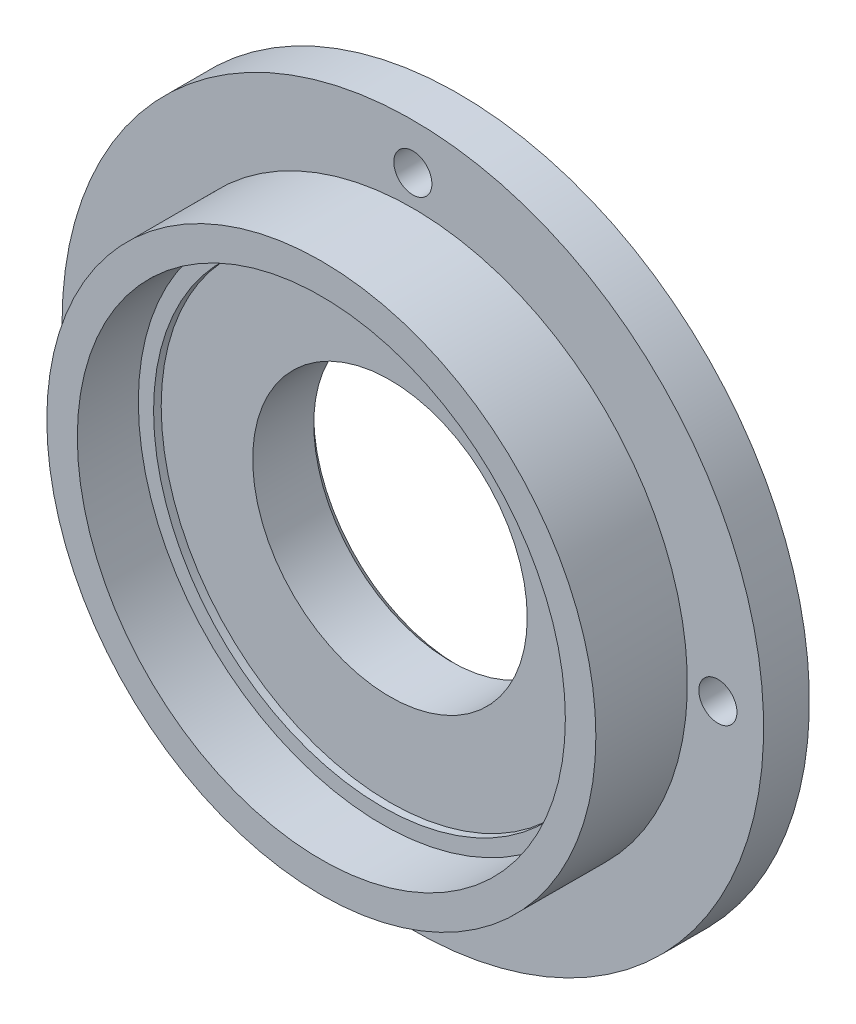
SolidWorks part; units mm, degrees
material "6061-T6 (SS)"
ref_plane "前视基准面" through (0, 0, 0) normal (0, 0, 1) x (1, 0, 0)
ref_plane "上视基准面" through (0, 0, 0) normal (0, 1, 0) x (1, 0, 0)
ref_plane "右视基准面" through (0, 0, 0) normal (1, 0, 0) x (0, 0, -1)
sketch "草图1" plane through (0, 0, 0) normal (0, 0, 1) x (1, 0, 0)
  circle A1 centre (0, 0) radius 18
  dimension "D2" = 36
extrude "凸台-拉伸3" add sketch "草图1" along normal blind 9
sketch "草图4" plane through (0, 0, 9) normal (0, 0, 1) x (1, 0, 0)
  circle A0 centre (0, 0) radius 16
  dimension "D1" = 32
extrude "切除-拉伸1" cut sketch "草图4" against normal blind 4
sketch "草图5" plane through (0, 0, 5) normal (0, 0, 1) x (1, 0, 0)
  circle A0 centre (0, 0) radius 15
  dimension "D1" = 30
extrude "切除-拉伸2" cut sketch "草图5" against normal blind 0.5
sketch "草图7" plane through (0, 0, 4.5) normal (0, 0, 1) x (1, 0, 0)
  circle A0 centre (0, 0) radius 9
  dimension "D1" = 18
extrude "切除-拉伸3" cut sketch "草图7" against normal through all
sketch "草图8" [suppressed] plane through (0, 0, 0) normal (0, 0, -1) x (-1, 0, 0)
  point P0 (0, 12)
  point P4 (12, 0)
  point P5 (0, -12)
  point P6 (-12, 0)
  point P7 (0, 0)
  dimension "D2" = 12
  dimension "D1" = 4
hole_wizard "M3 螺纹孔1" [suppressed] positions "草图9" profile "草图10" tap size "M3" standard "GB"
sketch "草图9" [suppressed] plane through (0, 0, 0) normal (0, 0, -1) x (-1, 0, 0)
  point P0 (0, 12)
  point P3 (-12, 0)
  point P6 (0, -12)
  point P9 (12, 0)
sketch "草图10" plane through (0, 12, 0) normal (1, 0, 0) x (0, 1, 0)
  line L0 (0, 0) -> (0, 3)
  line L1 (0, 3) -> (1.25, 3)
  line L2 (1.25, 3) -> (1.25, 0)
  line L5 (1.25, 0) -> (0, 0)
  line L11 (0, -6.35) -> (0, 107.95) construction
  dimension "通孔螺纹孔钻头直径" = 2.5
  dimension "通孔螺纹孔钻头深度" = 3
cosmetic thread "孔螺蚊线1" [suppressed] parameters "D2"=3
cosmetic thread "孔螺蚊线2" [suppressed] parameters "D2"=3
cosmetic thread "孔螺蚊线3" [suppressed] parameters "D2"=3
cosmetic thread "孔螺蚊线4" [suppressed] parameters "D2"=3
sketch "草图11" plane through (0, 0, 0) normal (0, 0, -1) x (-1, 0, 0)
  circle A0 centre (0, 0) radius 18
  circle A1 centre (0, 0) radius 23
  dimension "D1" = 36
  dimension "D2" = 46
extrude "凸台-拉伸4" add sketch "草图11" against normal blind 3
chamfer "倒角2" distance 0.5 angle 45 1 edges at (9, 0, 0)
sketch "草图12" plane through (0, 0, 0) normal (0, 0, -1) x (-1, 0, 0)
  point P0 (0, 20)
  point P4 (20, 0)
  point P5 (0, -20)
  point P6 (-20, 0)
  point P7 (0, 0)
  dimension "D2" = 20
  dimension "D1" = 4
hole_wizard "M3 螺纹孔2" positions "草图13" profile "草图14" tap size "M3" standard "GB" end condition up to next
sketch "草图13" plane through (0, 0, 0) normal (0, 0, -1) x (-1, 0, 0)
  point P0 (0, 20)
  point P3 (-20, 0)
  point P6 (0, -20)
  point P9 (20, 0)
sketch "草图14" plane through (0, 20, 0) normal (1, 0, 0) x (0, 1, 0)
  line L0 (0, 0) -> (0, 3)
  line L1 (0, 3) -> (1.25, 3)
  line L2 (1.25, 3) -> (1.25, 0)
  line L5 (1.25, 0) -> (0, 0)
  line L11 (0, -6.35) -> (0, 107.95) construction
  dimension "通孔螺纹孔钻头直径" = 2.5
  dimension "通孔螺纹孔钻头深度" = 3
cosmetic thread "孔螺蚊线5"
cosmetic thread "孔螺蚊线6"
cosmetic thread "孔螺蚊线7"
cosmetic thread "孔螺蚊线8"
